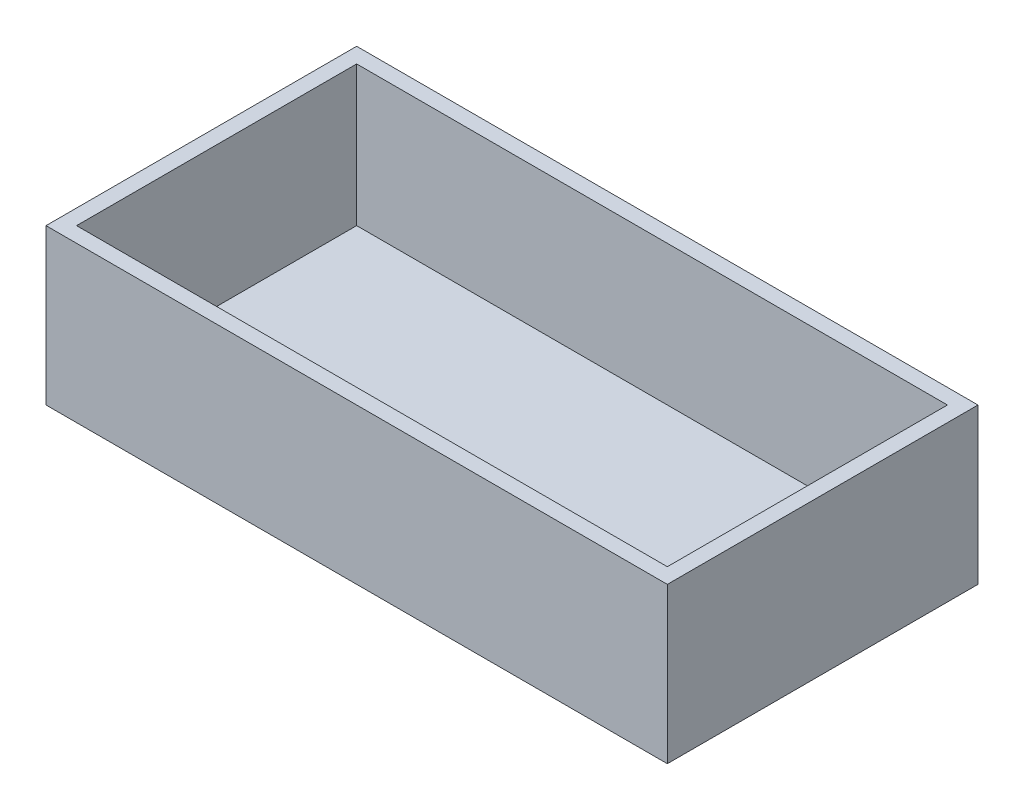
SolidWorks part; units mm, degrees
ref_plane "Front Plane" through (0, 0, 0) normal (0, 0, 1) x (1, 0, 0)
ref_plane "Top Plane" through (0, 0, 0) normal (0, 1, 0) x (1, 0, 0)
ref_plane "Right Plane" through (0, 0, 0) normal (1, 0, 0) x (0, 0, -1)
sketch "Sketch1" plane through (0, 0, 0) normal (0, 1, 0) x (1, 0, 0)
  line L1 (-101.6, -50.8) -> (101.6, -50.8)
  line L2 (-101.6, -50.8) -> (-101.6, 50.8)
  line L3 (-101.6, 50.8) -> (101.6, 50.8)
  line L4 (101.6, -50.8) -> (101.6, 50.8)
  line L5 (-101.6, -50.8) -> (101.6, 50.8) construction
  line L6 (-101.6, 50.8) -> (101.6, -50.8) construction
  point P0 (0, 0)
  dimension "D1" = 101.6
  dimension "D2" = 203.2
extrude "Boss-Extrude1" add sketch "Sketch1" along normal blind 50.8
shell "Shell3" thickness 5
